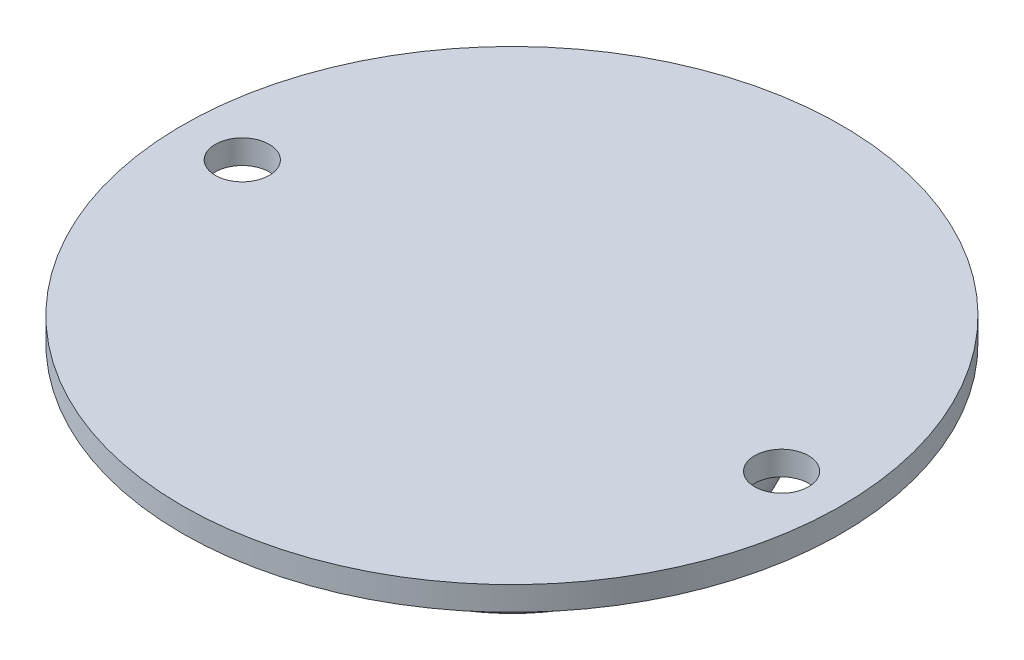
SolidWorks part; units mm, degrees
ref_plane "Front Plane" through (0, 0, 0) normal (0, 0, 1) x (1, 0, 0)
ref_plane "Top Plane" through (0, 0, 0) normal (0, 1, 0) x (1, 0, 0)
ref_plane "Right Plane" through (0, 0, 0) normal (1, 0, 0) x (0, 0, -1)
sketch "Sketch1" plane through (0, 0, 0) normal (0, 1, 0) x (1, 0, 0)
  circle A0 centre (0, 0) radius 17.5
  dimension "D1" = 35
extrude "Boss-Extrude1" add sketch "Sketch1" along normal blind 12
sketch "Sketch2" plane through (0, 12, 0) normal (0, 1, 0) x (1, 0, 0)
  circle A0 centre (0, 0) radius 27.5
  circle A1 centre (0, 0) radius 17.5 construction
  dimension "D1" = 10
extrude "Boss-Extrude2" add sketch "Sketch2" along normal blind 2
sketch "Sketch3" plane through (0, 0, 0) normal (0, -1, 0) x (-1, 0, 0)
  line L1 (2.25, 21.9035) -> (-2.25, 21.9035)
  line L2 (2.25, 21.9035) -> (2.25, -21.9035)
  line L3 (2.25, -21.9035) -> (-2.25, -21.9035)
  line L4 (-2.25, 21.9035) -> (-2.25, -21.9035)
  line L5 (2.25, 21.9035) -> (-2.25, -21.9035) construction
  line L6 (2.25, -21.9035) -> (-2.25, 21.9035) construction
  point P0 (0, 0)
  dimension "D1" = 4.5
extrude "Cut-Extrude2" cut sketch "Sketch3" against normal up to surface (12 mm away) up to face at (0, 12, 17.5)
fillet "Fillet1" radius 10 2 edges at (-17.5, 0, 0) (17.5, 0, 0)
sketch "Sketch4" plane through (0, 12, 0) normal (0, -1, 0) x (-1, 0, 0)
  line L0 (-27.5, 0) -> (27.5, 0) construction
  circle A0 centre (0, 0) radius 27.5 construction
  circle A1 centre (-22.5, 0) radius 2.25
  circle A2 centre (22.5, 0) radius 2.25
  dimension "D1" = 4.5
  dimension "D2" = 4.5
  dimension "D3" = 5
  dimension "D4" = 5
extrude "Cut-Extrude3" cut sketch "Sketch4" against normal blind 101.6
